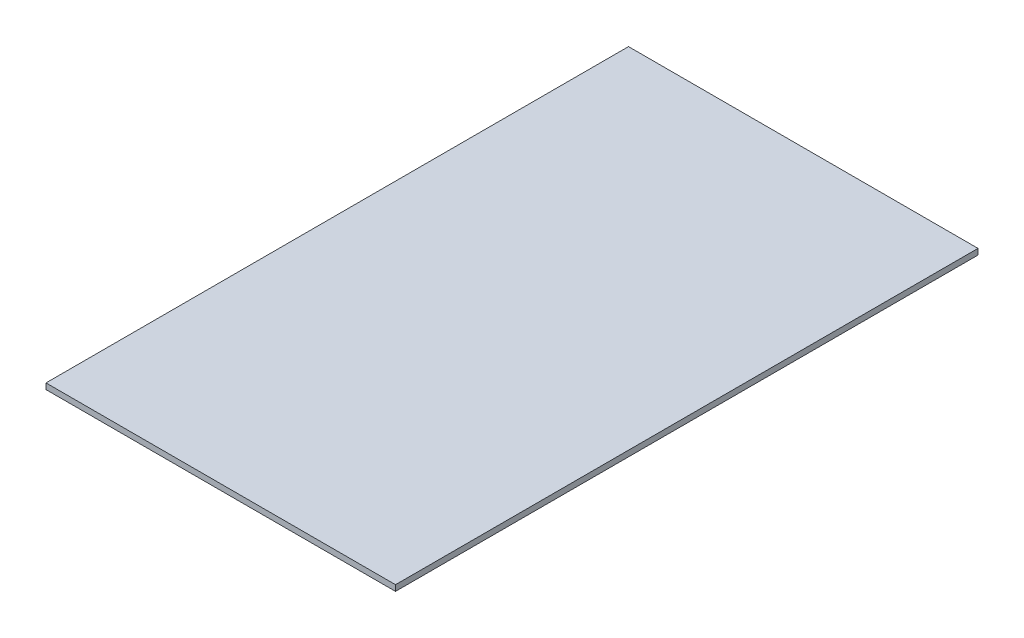
SolidWorks part; units mm, degrees
ref_plane "前视基准面" through (0, 0, 0) normal (0, 0, 1) x (1, 0, 0)
ref_plane "上视基准面" through (0, 0, 0) normal (0, 1, 0) x (1, 0, 0)
ref_plane "右视基准面" through (0, 0, 0) normal (1, 0, 0) x (0, 0, -1)
sketch "草图1" plane through (0, 0, 0) normal (0, 1, 0) x (1, 0, 0)
  line L1 (-600, 600) -> (600, 600)
  line L2 (-600, 600) -> (-600, -600)
  line L3 (-600, -600) -> (600, -600)
  line L4 (600, 600) -> (600, -600)
extrude "凸台-拉伸1" add sketch "草图1" along normal blind 20 contours L2 L3 L4 L1
sketch "草图6" plane through (0, 20, 0) normal (0, 1, 0) x (1, 0, 0)
  line L1 (-600, -600) -> (600, -600)
  line L2 (-600, -600) -> (-600, -1400)
  line L3 (-600, -1400) -> (600, -1400)
  line L4 (600, -600) -> (600, -1400)
extrude "凸台-拉伸3" add sketch "草图6" against normal blind 20
scale "缩放比例1" scale about origin uniform scaling yes scale factor 1.7
sketch "草图7" plane through (0, 34, 0) normal (0, 1, 0) x (1, 0, 0)
  point P0 (-935, 935)
  point P1 (0, 935)
  point P3 (935, 935)
  point P5 (-935, 0)
  point P7 (935, 0)
  point P9 (-935, -935)
  point P11 (0, -935)
  point P13 (935, -935)
  point P15 (-2525.3896, 0)
